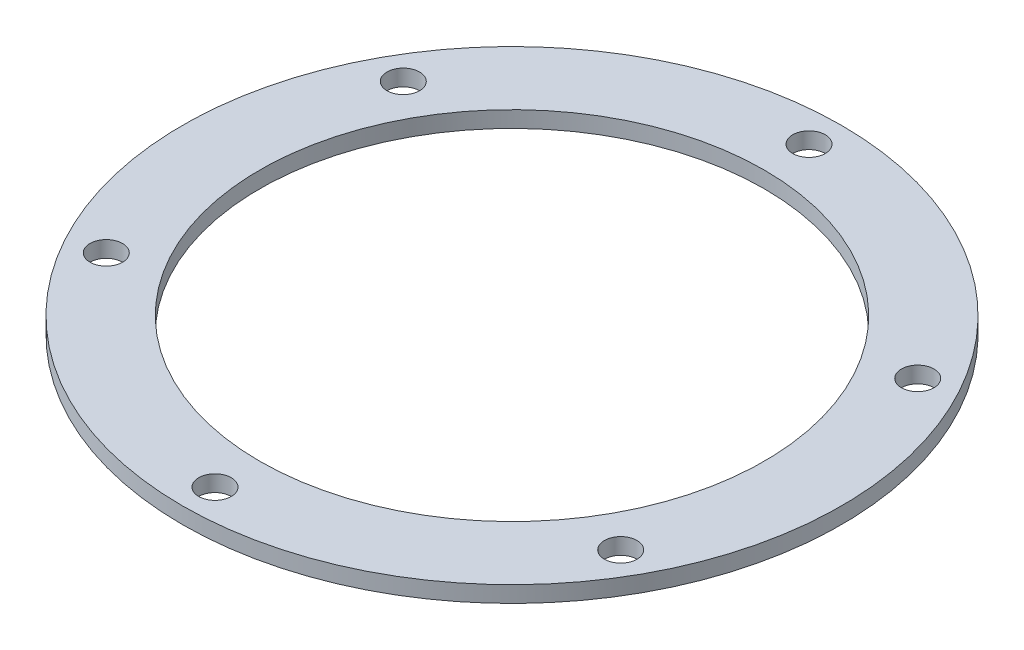
SolidWorks part; units mm, degrees
material "ABS"
ref_plane "Front Plane" through (0, 0, 0) normal (0, 0, 1) x (1, 0, 0)
ref_plane "Top Plane" through (0, 0, 0) normal (0, 1, 0) x (1, 0, 0)
ref_plane "Right Plane" through (0, 0, 0) normal (1, 0, 0) x (0, 0, -1)
sketch "Sketch1" plane through (0, 0, 0) normal (0, 1, 0) x (1, 0, 0)
  circle A0 centre (0, 0) radius 40.5
  circle A1 centre (0, 0) radius 31
  circle A2 centre (0, 0) radius 36.5 construction
  circle A3 centre (0, 36.5) radius 2
  circle A4 centre (31.6099, 18.25) radius 2
  circle A5 centre (31.6099, -18.25) radius 2
  circle A6 centre (0, -36.5) radius 2
  circle A7 centre (-31.6099, -18.25) radius 2
  circle A8 centre (-31.6099, 18.25) radius 2
  point P19 (0, 0)
  dimension "D1" = 81
  dimension "D2" = 62
  dimension "D3" = 73
  dimension "D4" = 4
  dimension "D5" = 6
extrude "Boss-Extrude1" add sketch "Sketch1" against normal mid plane 2
equation "\"Ns\" = 33"
equation "\"Np\" = 45"
equation "\"Nr\" = 123"
equation "\"num_planet\" = 3"
equation "\"module\" = 0.5"
equation "\"pressure angle\" = 20.0"
equation "\"motor_mount_hole_PCD\" = 32"
equation "\"motor_mount_hole_dia\" = 4"
equation "\"motor_mount_hole_num\" = 4"
equation "\"motor_output_hole_PCD\" = 22"
equation "\"motor_output_hole_dia\" = 3"
equation "\"motor_output_hole_num\" = 4"
equation "\"motor_OD\" = 72"
equation "\"motor_height\" = 27"
equation "\"wire_slot_dist_from_center\" = 30"
equation "\"wire_slot_length\" = 10"
equation "\"wire_slot_radius\" = 2.5"
equation "\"h_a\" = 0.5"
equation "\"h_b\" = 0.625"
equation "\"clr_tip_root\" = 0.125"
equation "\"dp_s\" = 16.5"
equation "\"db_s\" = 15.50492824296749"
equation "\"fw_s_calc\" = 5.95406185839039"
equation "\"alpha_s\" = 0.8539582918412449"
equation "\"beta_s\" = 3.7466288708629643"
equation "\"dp_p\" = 22.5"
equation "\"db_p\" = 21.14308396768294"
equation "\"fw_p\" = 8.0"
equation "\"alpha_p\" = 0.8539582918412307"
equation "\"beta_p\" = 2.2920834163175385"
equation "\"pressure_angle\" = 20.0"
equation "\"h_f\" = 0.625"
equation "\"dp_r\" = 61.5"
equation "\"db_r\" = 57.79109617833337"
equation "\"fw_r\" = 8.0"
equation "\"alpha_r\" = 0.8539582918412414"
equation "\"beta_r\" = 3.171331217828824"
equation "\"bearing_ID\" = 50"
equation "\"bearing_OD\" = 65"
equation "\"bearing_height\" = 7"
equation "\"clearance_planet\" = 1.5"
equation "\"case_dist\" = 6.0"
equation "\"Motor_case_OD_max\" = 96.5"
equation "\"case_mounting_PCD\" = 89.0"
equation "\"bearing mount thickness\" = 8"
equation "\"case_mounting_hole_dia\" = 3"
equation "\"output_mounting_PCD\" = 73"
equation "\"output_mounting_hole_dia\" = 4"
equation "\"clearance_case_mount_holes_shell_thickness\" = 1"
equation "\"motor_case_OD_base\" = 87.0"
equation "\"sec_carrier_thickness\" = 5"
equation "\"sun_coupler_hub_thickness\" = 4"
equation "\"clearance_sun_coupler_sec_carrier\" = 1.5"
equation "\"clearance_motor_and_case\" = 5"
equation "\"Motor_case_thickness\" = 2.5"
equation "\"Motor_case_ID\" = 82"
equation "\"case_mounting_hole_shift\" = 1.0"
equation "\"output_mounting_nut_wrench_size\" = 7"
equation "\"output_mounting_nut_thickness\" = 3.2"
equation "\"case_mounting_hole_allen_socket_dia\" = 5.5"
equation "\"output_mounting_nut_depth\" = 3"
equation "\"case_mounting_bolt_depth\" = 4.5"
equation "\"ring_radial_thickness\" = 5"
equation "\"ring_OD\" = 71.5"
equation "\"ring_to_chamfer_clearance\" = 2"
equation "\"Motor_case_OD_base_to_chamfer\" = 5"
equation "\"pattern_offset_from_motor_case_OD_base\" = 3"
equation "\"pattern_bulge_dia\" = 3"
equation "\"pattern_num_bulge\" = 18"
equation "\"pattern_depth\" = 2"
equation "\"case_mounting_wrench_size\" = 5.5"
equation "\"case_mounting_nut_clearance\" = 2"
equation "\"base_plate_thickness\" = 4"
equation "\"case_mounting_nut_thickness\" = 2.4"
equation "\"case_mounting_surface_height\" = 4"
equation "\"central_hole_offset_from_motor_mount_PCD\" = 5"
equation "\"driver_upper_holes_dist_from_center\" = 23"
equation "\"driver_lower_holes_dist_from_center\" = 15"
equation "\"driver_side_holes_dist_from_center\" = 20"
equation "\"driver_mount_holes_dia\" = 2.5"
equation "\"driver_mount_inserts_OD\" = 3.5"
equation "\"driver_mount_thickness\" = 1.5"
equation "\"driver_mount_height\" = 4"
equation "\"air_flow_hole_offset\" = 3"
equation "\"planet_pin_bolt_dia\" = 5"
equation "\"planet_pin_socket_head_dia\" = 8.5"
equation "\"carrier_PCD\" = 39.0"
equation "\"planet_shaft_dia\" = 8"
equation "\"planet_shaft_step_offset\" = 1"
equation "\"carrier_trapezoidal_support_sun_offset\" = 5"
equation "\"carrier_trapezoidal_support_hole_PCD_offset_bearing_ID\" = 4"
equation "\"carrier_trapezoidal_support_hole_dia\" = 3"
equation "\"carrier_trapezoidal_support_hole_socket_head_dia\" = 5.5"
equation "\"carrier_bearing_step_width\" = 1.5"
equation "\"standard_clearance_1_5mm\" = 1.5"
equation "\"standard_fillet_1_5mm\" = 1.5"
equation "\"sun_shaft_bearing_OD\" = 16"
equation "\"sun_shaft_bearing_width\" = 5"
equation "\"standard_bearing_insertion_chamfer\" = 0.5"
equation "\"carrier_trapezoidal_support_hole_wrench_size\" = 5.5"
equation "\"planet_pin_bolt_wrench_size\" = 8"
equation "\"planet_bearing_OD\" = 12"
equation "\"planet_bearing_width\" = 3.5"
equation "\"planet_bore\" = 10"
equation "\"sun_shaft_bearing_ID\" = 8"
equation "\"sun_hub_dia\" = 31.0"
equation "\"sun_central_bolt_dia\" = 5"
equation "\"sun_central_bolt_socket_head_dia\" = 8.5"
equation "\"fw_s_used\" = 16.0"
equation "\"motor_output_hole_CSK_OD\" = 6"
equation "\"motor_output_hole_CSK_head_height\" = 1.5"
equation "\"bearing_retainer_thickness\" = 2"
equation "\"stg1_stg2_mounting_pattern_width\" = 12"
equation "\"stg1_stg2_allen_socket_head_dia\" = 7.0"
equation "\"stg1_stg2_mounting_hole_dia\" = 4"
equation "\"stg1_carrier_stg2_sun_coupling_pcd\"= 20"
equation "\"stg1_carrier_stg2_sun_coupling_dia\"= 4"
equation "\"stg1_carrier_stg2_sun_coupling_nut_wrench\"= 7"
equation "\"stg1_carrier_stg2_sun_coupling_num\"= 3"
equation "\"stg1_carrier_stg2_sun_coupling_nut_thickness\"= 3.2"
equation "\"Ns2\"= 20"
equation "\"Np2\"= 40"
equation "\"Nr2\"= \"Ns2\" + 2 * \"Np2\""
equation "\"module2\"= 0.8"
equation "\"stg1_stg2_mounting_extra_width\" = 5.25"
equation "\"dp_s2\"= \"module2\" * \"Ns2\"'PCD"
equation "\"db_s2\"= \"dp_s2\" * cos ( \"pressure angle\" )'base CD"
equation "\"fw_s_calc2\"= 13mm'face width"
equation "\"alpha_s2\"= sqr ( \"dp_s2\" ^ 2 - \"db_s2\" ^ 2 ) / \"db_s2\" * 180 / pi - \"pressure angle\""
equation "\"beta_s2\"= ( 360 / ( 4 * \"Ns2\" ) - \"alpha_s2\" ) * 2"
equation "\"fw_s_used2\"= \"fw_p2\" + \"clearance_planet\" + \"sec_carrier_thickness\" + \"standard_clearance_1_5mm\""
equation "\"fw_p2\"= 11.5"
equation "\"D1@Sketch1\"=\"bearing_OD\" + \"bearing mount thickness\" * 2 "
equation "\"D2@Sketch1\"= \"bearing_OD\" - \"standard_clearance_1_5mm\"*2"
equation "\"D3@Sketch1\"= \"output_mounting_PCD\""
equation "\"D4@Sketch1\"=\"stg1_stg2_mounting_hole_dia\""
equation "\"D1@Boss-Extrude1\"=\"bearing_retainer_thickness\""
equation "\"Ns1\" = 33"
equation "\"Np1\" = 45"
equation "\"Nr1\" = 123"
equation "\"module1\" = 0.5"
equation "\"bearing1_ID\" = 50"
equation "\"bearing1_OD\" = 65"
equation "\"bearing1_height1\" = 7"
equation "\"bearing mount thickness1\" = 8"
equation "\"output_mounting_PCD1\" = 73"
equation "\"num_planet1\" = 3"
